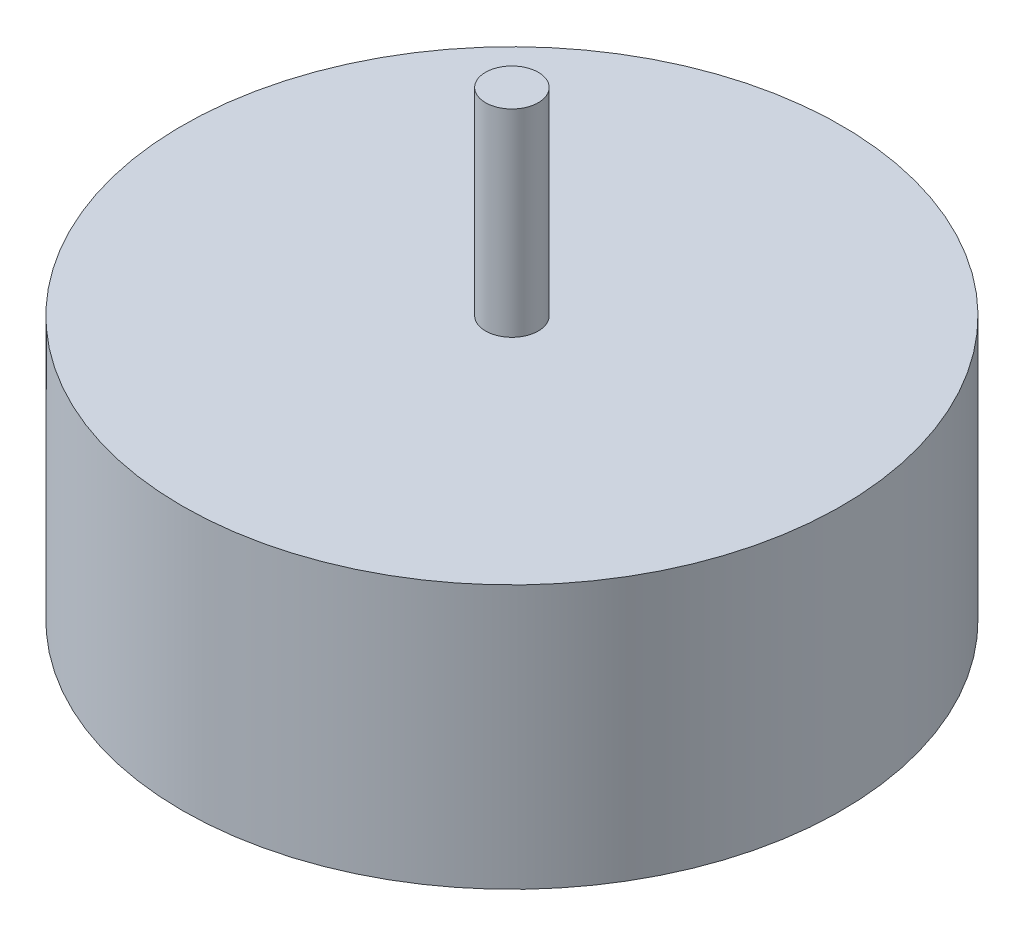
SolidWorks part; units mm, degrees
ref_plane "Front Plane" through (0, 0, 0) normal (0, 0, 1) x (1, 0, 0)
ref_plane "Top Plane" through (0, 0, 0) normal (0, 1, 0) x (1, 0, 0)
ref_plane "Right Plane" through (0, 0, 0) normal (1, 0, 0) x (0, 0, -1)
sketch "Sketch1" plane through (0, 0, 0) normal (0, 0, 1) x (1, 0, 0)
  line L0 (-1000, 0) -> (49000, 0)
  line L1 (0, -1000) -> (0, 49000)
  line L2 (0, 50) -> (0, 0)
  line L3 (0, 0) -> (50, 0)
  line L4 (50, -20) -> (50, 20)
  line L5 (50, 20) -> (4, 20)
  line L6 (4, 20) -> (4, 50)
  line L7 (4, 50) -> (0, 50)
  line L8 (50, -20) -> (4, -20)
  line L9 (4, -20) -> (4, -50)
  line L10 (4, -50) -> (0, -50)
  line L11 (0, 50) -> (0, -50)
  dimension "D1" = 4
  dimension "D2" = 50
  dimension "D3" = 20
  dimension "D4" = 30
revolve "Revolve3" add sketch "Sketch1" angle 360 about L11
